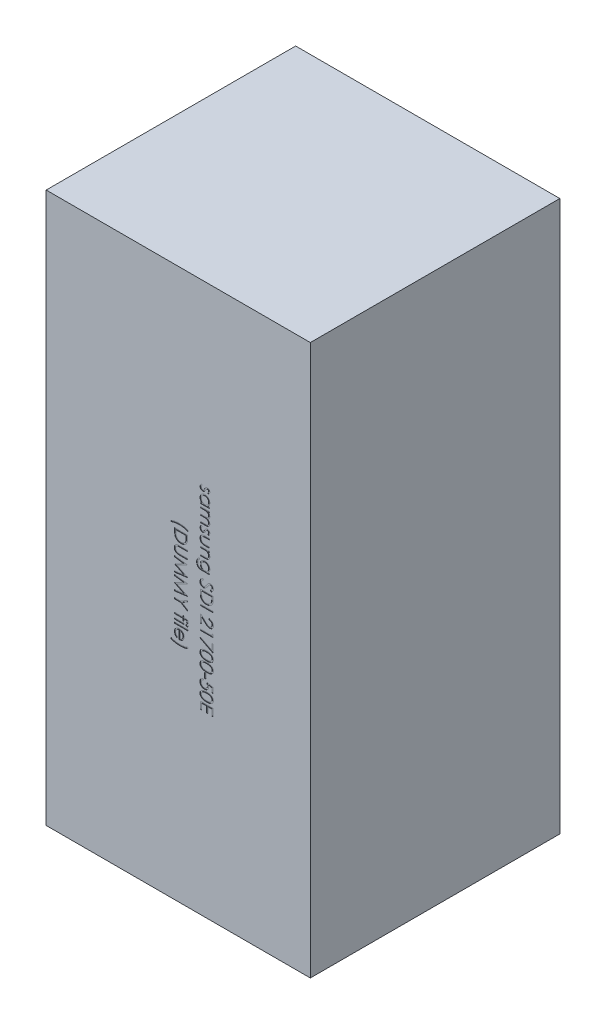
SolidWorks part; units mm, degrees
ref_plane "정면" through (0, 0, 0) normal (0, 0, 1) x (1, 0, 0)
ref_plane "윗면" through (0, 0, 0) normal (0, 1, 0) x (1, 0, 0)
ref_plane "우측면" through (0, 0, 0) normal (1, 0, 0) x (0, 0, -1)
sketch "스케치1" plane through (0, 0, 0) normal (0, 0, 1) x (1, 0, 0)
  line L1 (-36, 75) -> (36, 75)
  line L2 (-36, 75) -> (-36, -75)
  line L3 (-36, -75) -> (36, -75)
  line L4 (36, 75) -> (36, -75)
  line L5 (-36, 75) -> (36, -75) construction
  line L6 (-36, -75) -> (36, 75) construction
  point P0 (0, 0)
  dimension "D1" = 150
  dimension "D2" = 72
extrude "보스-돌출1" add sketch "스케치1" along normal blind 68
sketch "스케치2" plane through (0, 0, 68) normal (0, 0, 1) x (1, 0, 0)
  line L0 (6, 75) -> (6, -75) construction
  line L1 (36, 75) -> (-36, 75) construction
  line L2 (-36, -75) -> (36, -75) construction
  line L3 (36, -75) -> (36, 75) construction
  text T0 "samsung SDI 21700-50E\r\n(DUMMY file)"
  dimension "D1" = 30
extrude "컷-돌출1" cut sketch "스케치2" against normal blind 0.1
